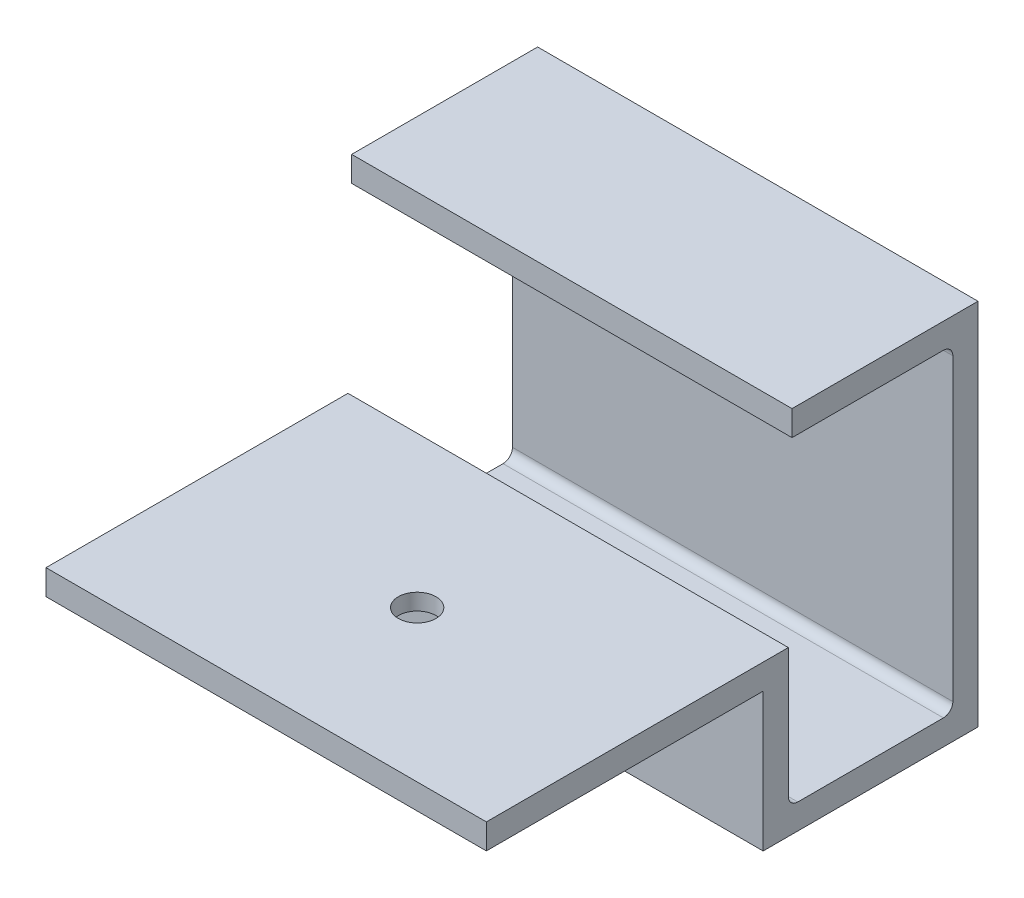
SolidWorks part; units mm, degrees
ref_plane "Front Plane" through (0, 0, 0) normal (0, 0, 1) x (1, 0, 0)
ref_plane "Top Plane" through (0, 0, 0) normal (0, 1, 0) x (1, 0, 0)
ref_plane "Right Plane" through (0, 0, 0) normal (1, 0, 0) x (0, 0, -1)
sketch "Sketch2" plane through (0, 0, 0) normal (1, 0, 0) x (0, 0, -1)
  line L1 (-24, 2) -> (24, 2)
  line L2 (-24, 2) -> (-24, -2)
  line L3 (-24, -2) -> (24, -2)
  line L4 (24, 2) -> (24, -2)
  line L5 (-24, 2) -> (24, -2) construction
  line L6 (-24, -2) -> (24, 2) construction
  line L7 (24, 2) -> (20, 2)
  line L8 (24, 2) -> (24, -24.01)
  line L9 (24, -24.01) -> (20, -24.01)
  line L10 (20, 2) -> (20, -24.01)
  line L11 (24, -24.01) -> (50.15, -24.01)
  line L12 (24, -24.01) -> (24, -20.01)
  line L13 (24, -20.01) -> (50.15, -20.01)
  line L14 (50.15, -24.01) -> (50.15, -20.01)
  line L15 (50.15, -24.01) -> (54.15, -24.01)
  line L16 (50.15, -24.01) -> (50.15, 34.6)
  line L17 (50.15, 34.6) -> (54.15, 34.6)
  line L18 (54.15, -24.01) -> (54.15, 34.6)
  line L19 (50.15, 34.6) -> (24.59, 34.6)
  line L20 (50.15, 34.6) -> (50.15, 30.6)
  line L21 (50.15, 30.6) -> (24.59, 30.6)
  line L22 (24.59, 34.6) -> (24.59, 30.6)
  point P0 (0, 0)
  dimension "D1" = 48
  dimension "D2" = 4
  dimension "D3" = 26.01
  dimension "D4" = 4
  dimension "D5" = 26.15
  dimension "D6" = 4
  dimension "D7" = 58.61
  dimension "D8" = 4
  dimension "D9" = 25.56
  dimension "D10" = 4
extrude "Boss-Extrude1" add sketch "Sketch2" along normal blind 70 contours L10 L1 L2 L3 | L1 L10 L3 L4 | L3 L10 L9 L8 | L11 L14 L13 L8 | L15 L18 L17 L16 L14 | L20 L19 L22 L21
fillet "Fillet1" radius 1.5 3 edges at (35, -20.01, -50.15) (35, -20.01, -24) (35, 30.6, -50.15)
sketch "Sketch3" plane through (0, 2, 0) normal (0, 1, 0) x (1, 0, 0)
  line L0 (0, 0) -> (70, 0) construction
  line L1 (0, -24) -> (0, 24) construction
  line L2 (70, -24) -> (70, 24) construction
  circle A0 centre (35, 0) radius 3
  dimension "D1" = 6
extrude "Cut-Extrude1" cut sketch "Sketch3" against normal through all
sketch "Sketch4" plane through (0, -2, 0) normal (0, 1, 0) x (1, 0, 0)
  circle A0 centre (35, 0) radius 5
  dimension "D1" = 10
extrude "Cut-Extrude2" cut sketch "Sketch4" along normal blind 1.4
equation "\"D2@Sketch2\"=4"
equation "\"D4@Sketch2\"=\"D2@Sketch2\""
equation "\"D3@Sketch2\"=21.71+\"D4@Sketch2\"+0.3"
equation "\"D5@Sketch2\"=25.55+0.6"
equation "\"D6@Sketch2\"=\"D2@Sketch2\""
equation "\"D7@Sketch2\"=50.31+\"D2@Sketch2\"*2+0.3"
equation "\"D8@Sketch2\"=\"D2@Sketch2\""
equation "\"D10@Sketch2\"=\"D2@Sketch2\""
